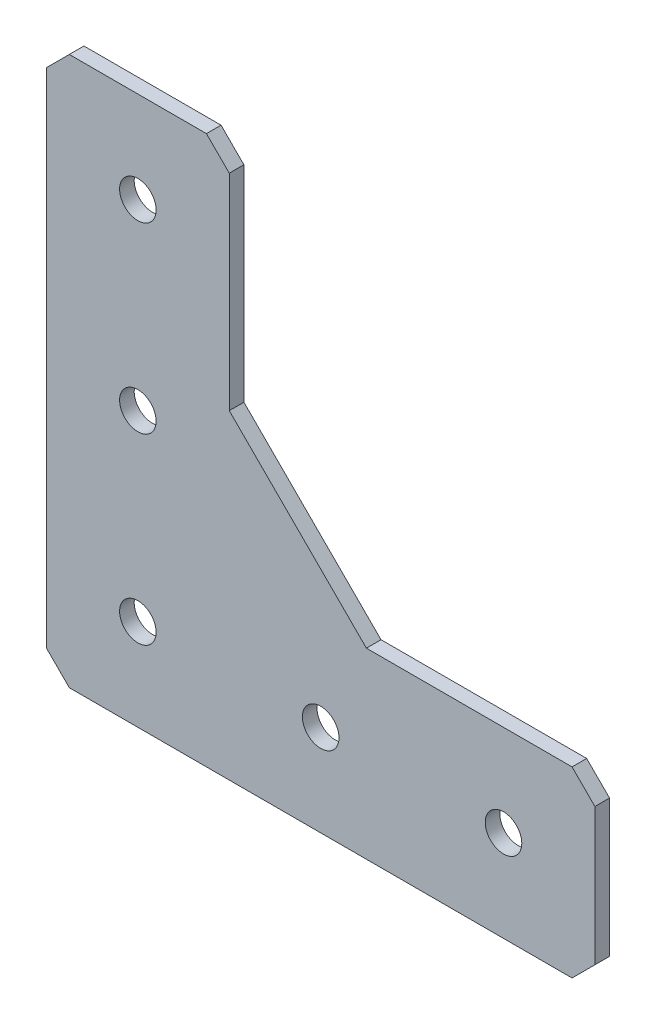
SolidWorks part; units mm, degrees
ref_plane "Front" through (0, 0, 0) normal (0, 0, 1) x (1, 0, 0)
ref_plane "Top" through (0, 0, 0) normal (0, 1, 0) x (1, 0, 0)
ref_plane "Right" through (0, 0, 0) normal (1, 0, 0) x (0, 0, -1)
sketch "Sketch1" plane through (0, 0, 0) normal (0, 0, 1) x (1, 0, 0)
  line B0 (76.2, 3.175) -> (76.2, 22.225)
  line B1 (73.025, 0) -> (76.2, 3.175)
  line B2 (3.175, 0) -> (73.025, 0)
  line B3 (0, 3.175) -> (3.175, 0)
  line B4 (0, 73.025) -> (0, 3.175)
  line B5 (3.175, 76.2) -> (0, 73.025)
  line B6 (22.225, 76.2) -> (3.175, 76.2)
  line B7 (25.4, 73.025) -> (22.225, 76.2)
  line B8 (25.4, 44.45) -> (25.4, 73.025)
  line B9 (44.45, 25.4) -> (25.4, 44.45)
  line B10 (73.025, 25.4) -> (44.45, 25.4)
  line B11 (76.2, 22.225) -> (73.025, 25.4)
  circle B12 centre (12.7, 12.7) radius 2.54
  circle B13 centre (12.7, 38.1) radius 2.54
  circle B14 centre (12.7, 63.5) radius 2.54
  circle B15 centre (38.1, 12.7) radius 2.54
  circle B16 centre (63.5, 12.7) radius 2.54
sketch_block_instance "Block1-1"
sketch_block "Block1"
extrude "Boss-Extrude1" add sketch "Sketch1" along normal mid plane 2.032
